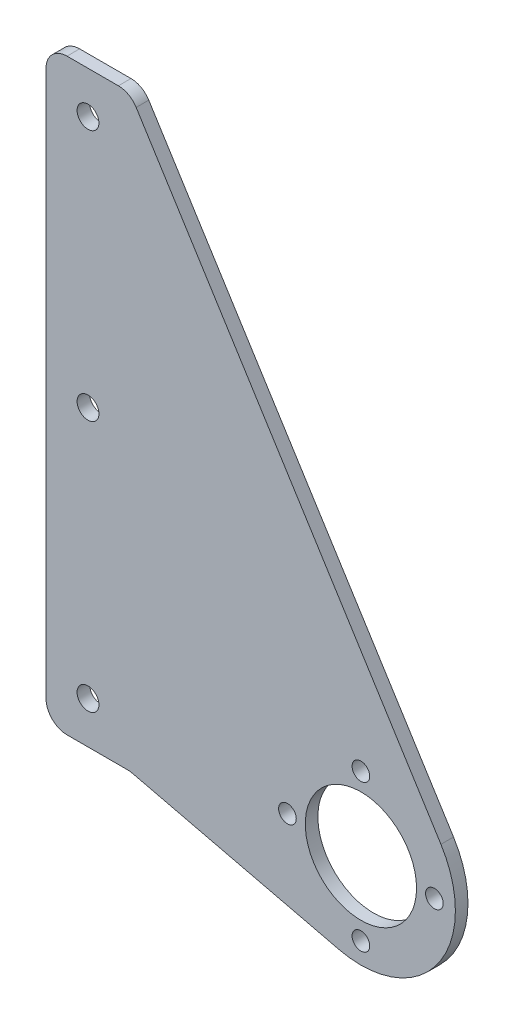
SolidWorks part; units mm, degrees
ref_plane "正面" through (0, 0, 0) normal (0, 0, 1) x (1, 0, 0)
ref_plane "平面" through (0, 0, 0) normal (0, 1, 0) x (1, 0, 0)
ref_plane "右側面" through (0, 0, 0) normal (1, 0, 0) x (0, 0, -1)
sketch "ｽｹｯﾁ2" plane through (0, 0, 0) normal (0, 0, 1) x (1, 0, 0)
  line L0 (17.5, 0) -> (-17.5, 0) construction
  line L1 (0, -17.5) -> (0, 17.5) construction
  line L2 (0, 0) -> (-55, 60) construction
  line L3 (-65, 0) -> (-65, 60) construction
  line L4 (-65, 60) -> (-65, 120) construction
  line L5 (-75, 130) -> (-75, -10)
  line L6 (-75, -10) -> (-55, -10)
  line L7 (-75, 130) -> (-55, 130)
  line L8 (-55, 130) -> (-55, -10) construction
  line L9 (-55, 130) -> (19.0594, 11.9578)
  line L10 (-55, -10) -> (-5.2255, -21.8848)
  line L11 (-75, 60) -> (-55, 60) construction
  line L12 (0, -22.5) -> (-75, -22.5) construction
  line L13 (-75, -22.5) -> (-75, -10) construction
  line L14 (0, -50) -> (-75, -50) construction
  line L15 (-75, -50) -> (-75, -10) construction
  circle A0 centre (0, 0) radius 13.25
  circle A1 centre (0, 17.5) radius 2.1
  circle A2 centre (17.5, 0) radius 2.1
  circle A3 centre (0, -17.5) radius 2.1
  circle A4 centre (-17.5, 0) radius 2.1
  circle A5 centre (-65, 60) radius 2.6
  circle A6 centre (-65, 120) radius 2.6
  circle A7 centre (-65, 0) radius 2.6
  arc A8 (-5.2255, -21.8848) -> (19.0594, 11.9578) centre (0, 0) ccw
  circle A9 centre (0, 0) radius 50 construction
  point P6 (0, 0)
  point P9 (0, 0)
  point P29 (-65, 60)
  dimension "D1" = 26.5
  dimension "D2" = 4.2
  dimension "D3" = 5.2
  dimension "D4" = 60
  dimension "D5" = 60
  dimension "D8" = 22.5
  dimension "D9" = 20
  dimension "D11" = 10
  dimension "D12" = 100
  dimension "D13" = 75
  dimension "D6" = 90
  dimension "D7" = 35
  dimension "D10" = 10
  dimension "D14" = 40
extrude "ﾎﾞｽ - 押し出し1" add sketch "ｽｹｯﾁ2" along normal blind 3
fillet "ﾌｨﾚｯﾄ3" radius 5 4 edges at (-55, 130, 1.5) (-55, -10, 1.5) (-75, -10, 1.5) (-75, 130, 1.5)
